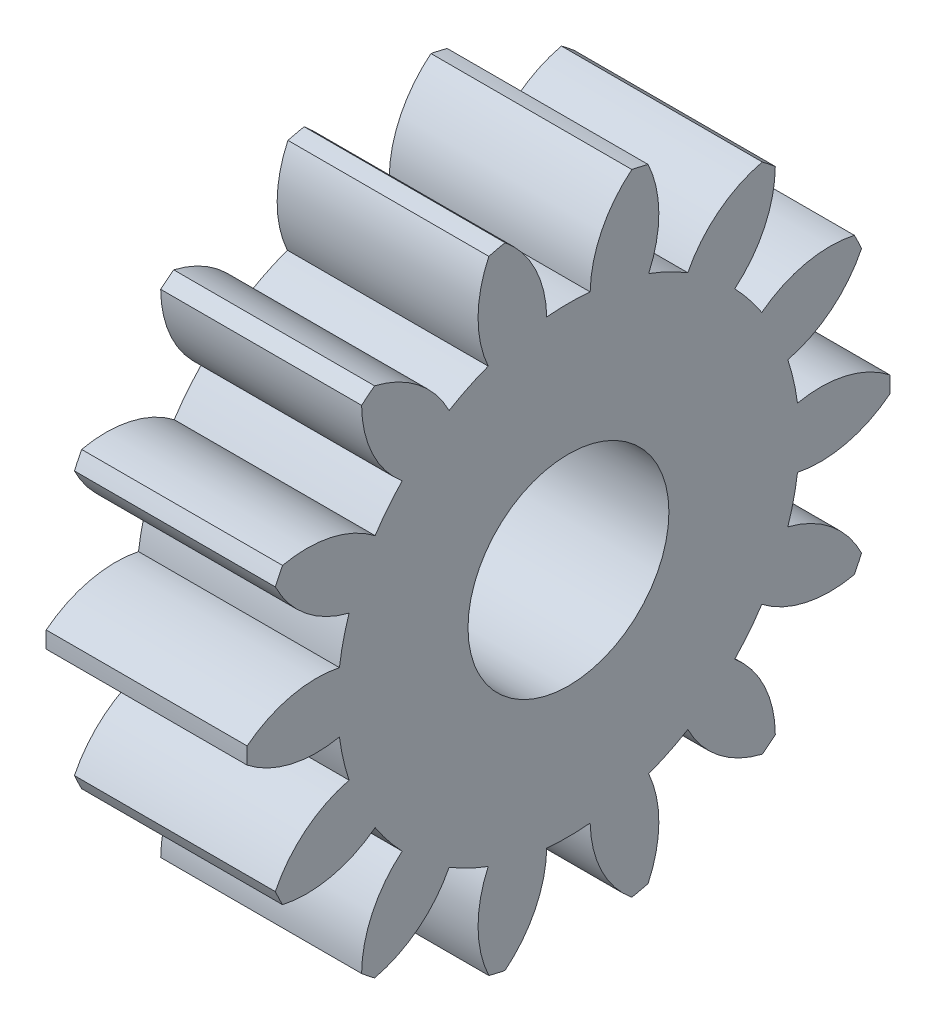
SolidWorks part; units mm, degrees
ref_plane "Plane1" through (0, 0, 0) normal (0, 0, 1) x (1, 0, 0)
ref_plane "Plane2" through (0, 0, 0) normal (0, 1, 0) x (1, 0, 0)
ref_plane "Plane3" through (0, 0, 0) normal (1, 0, 0) x (0, 0, -1)
sketch "HoldingSke" plane through (0, 0, 0) normal (0, 1, 0) x (1, 0, 0)
  line L0 (0, 0) -> (0.9703, -0.2419)
  line L1 (-15, 0) -> (100, 0) construction
  line L2 (0, 0) -> (-2.1039, 2.3779)
  line L3 (0, 0) -> (-11.863, 4.5341)
  line L4 (0, 0) -> (8.3795, 2.0892)
  line L5 (0, 0) -> (-46.8476, -17.4728)
  line L6 (0, 0) -> (-4.1448, -2.7965)
  line L7 (-2.1039, 2.3779) -> (8.6586, 51.2059)
  line L8 (-76.2, 54.61) -> (-75.3, 54.61)
  line L9 (-71.009, 38.7566) -> (-53.1078, 45.2721)
  line L10 (-76.2, 71.12) -> (104.1128, 71.12)
  line L11 (0, 0) -> (-5, 0)
  line L12 (-76.2, 101.6) -> (-76.162, 101.6)
  line L13 (24.9733, 27.94) -> (52.9518, 28.4284)
  line L14 (24.9733, 27.94) -> (24.9743, 27.94)
  line L15 (24.9733, 27.94) -> (100.4006, 29.5858)
  line L16 (-63.627, -1) -> (-12.827, -1)
  circle A0 centre (0, 0) radius 2.5
  circle A1 centre (0, 0) radius 5.749
  circle A2 centre (0, 0) radius 37.5
  circle A3 centre (0, 0) radius 2.5
  dimension "MHD" = 11.498
  dimension "Hub_dia" = 75
  dimension "Bore" = 5
  dimension "MBD" = 5
  dimension "Num_teeth" = 14
  dimension "Pitch" = 1
  dimension "Overall_len" = 50
  dimension "Show_teeth" = 14
  dimension "Thickness" = 5
  dimension "OAL" = 50.0001
  dimension "T_dim" = 0.9
  dimension "Ap" = 20
  dimension "H" = 19.05
  dimension "Pitch_radius" = 180.3128
  dimension "Width" = 5
  dimension "Backlash" = 0.038
  dimension "Addendum_fac" = 1
  dimension "Dedendum_fac" = 1.25
  dimension "Clearance_fac" = 0.25
  dimension "Dedendum_add" = 0.001
  dimension "Module" = 1
sketch "BasProSke" plane through (0, 0, 0) normal (0, 1, 0) x (1, 0, 0)
  line L0 (-10, 0) -> (60, 0) construction
  line L1 (0, 0) -> (0, 8)
  line L2 (0, 0) -> (5, 0)
  line L3 (5, 0) -> (5, 8)
  line L4 (5, 8) -> (0, 8)
  dimension "Thickness" = 5
  dimension "Diameter" = 16
revolve "Base-Revolve" add sketch "BasProSke" angle 360 about L0
sketch "TooCutSke" plane through (0, 0, 0) normal (1, 0, 0) x (0, 0, -1)
  line L1 (0, 0) -> (0, 107) construction
  line L2 (0, 0) -> (-0.8502, 6.9482) construction
  line L3 (0, 0) -> (-3.0989, 13.5772) construction
  line L4 (-0.8502, 6.9482) -> (-1.5494, 6.7886) construction
  arc A0 (0.5404, 5.7235) -> (-0.5404, 5.7235) centre (0, 0) ccw
  arc A1 (1.6036, 7.8636) -> (-1.6036, 7.8636) centre (0, 0) ccw
  circle A2 centre (0, 0) radius 7 construction
  circle A3 centre (0, 0) radius 6.5778 construction
  arc A4 (-0.5404, 5.7235) -> (-1.6036, 7.8636) centre (-3.3398, 5.6669) ccw
  arc A5 (1.6036, 7.8636) -> (0.5404, 5.7235) centre (3.3398, 5.6669) ccw
  dimension "Root_dia" = 11.498
  dimension "Overcut_dia" = 16.0508
  dimension "Pitch_dia" = 14
  dimension "Base_dia" = 13.1557
  dimension "Flank_rad" = 2.8
  dimension "Half_ang" = 12.857
  dimension "Half_CT" = 0.7173
extrude "ToothCut" cut sketch "TooCutSke" along normal through all
fillet "Breaks" [suppressed] radius 0.02
fillet "RootFillets" [suppressed] radius 0.251
pattern_circular "TeethCuts" count 14 every 25.714 about axis through (-10, 0, 0) along (1, 0, 0) of "ToothCut", "RootFillets", "Breaks"
sketch "HubNeaOneSke" plane through (0, 0, 0) normal (-1, 0, 0) x (0, 0, 1)
  circle A0 centre (0, 0) radius 5.749
  dimension "Diameter" = 11.498
extrude "HubNearOne" [suppressed] add sketch "HubNeaOneSke" along normal blind 45.0001
sketch "HubNeaBotSke" plane through (0, 0, 0) normal (-1, 0, 0) x (0, 0, 1)
  circle A0 centre (0, 0) radius 5.749
  dimension "Diameter" = 11.498
extrude "HubNearBoth" [suppressed] add sketch "HubNeaBotSke" along normal blind 22.5
ref_plane "FarPln" through (5, 0, 0) normal (1, 0, 0) x (0, 0, -1)
sketch "HubFarSke" plane through (5, 0, 0) normal (1, 0, 0) x (0, 0, -1)
  circle A0 centre (0, 0) radius 5.749
  dimension "Diameter" = 11.498
extrude "HubFar" [suppressed] add sketch "HubFarSke" along normal blind 22.5
sketch "BorSke" plane through (0, 0, 0) normal (1, 0, 0) x (0, 0, -1)
  circle A0 centre (0, 0) radius 2.5
  dimension "Diameter" = 5
extrude "Bore" cut sketch "BorSke" along normal mid plane 100.0001
sketch "KeySke" plane through (0, 0, 0) normal (1, 0, 0) x (0, 0, -1)
  line L0 (-1, 0) -> (-1, 3.4)
  line L1 (-1, 3.4) -> (1, 3.4)
  line L2 (1, 3.4) -> (1, 0)
  line L3 (0, 0) -> (0, 34) construction
  line L4 (-1, 0) -> (1, 0)
  dimension "Offset" = 3.4
  dimension "Width" = 2
extrude "Keyway" [suppressed] cut sketch "KeySke" along normal mid plane 100.0001
pattern_circular "Keyway2" [suppressed] count 2 every 90 about axis through (-10, 0, 0) along (1, 0, 0)
equation "' \"Module@HoldingSke\" = 6.35"
equation "' \"Num_teeth@HoldingSke\" = 12"
equation "' \"Ap@HoldingSke\" =  20"
equation "' \"Ap@HoldingSke\" = 20"
equation "' \"Width@HoldingSke\" = 0.5 * 25.4"
equation "' \"Hub_dia@HoldingSke\"= 1 * 25.4"
equation "' \"Hub_dia@HoldingSke\" = 1 * 25.4"
equation "' \"Overall_len@HoldingSke\" = 1.0 * 25.4"
equation "' \"Bore@HoldingSke\" = 0.75 * 25.4"
equation "' \"T_dim@HoldingSke\" = 0.1 * 25.4"
equation "' \"Width@KeySke\" = 0.25 * 25.4"
equation "' \"Show_teeth@HoldingSke\" = 13"
equation "' \"Backlash@HoldingSke\" = 0.009 * 25.4"
equation "' \"Addendum_fac@HoldingSke\" = 1.0"
equation "' \"Dedendum_fac@HoldingSke\" = 1.25"
equation "' \"Dedendum_add@HoldingSke\" = 0.00005 * 25.4"
equation "' \"Clearance_fac@HoldingSke\" = 0.25"
equation "\"Pitch@HoldingSke\" = 1 / \"Module@HoldingSke\""
equation "\"Overcut_dia@TooCutSke\" = (\"Num_teeth@HoldingSke\" + 2 * \"Addendum_fac@HoldingSke\") / \"Pitch@HoldingSke\" + 0.002 * 25.4"
equation "\"Pitch_dia@TooCutSke\" = \"Num_teeth@HoldingSke\" / \"Pitch@HoldingSke\""
equation "\"Base_dia@TooCutSke\" = \"Num_teeth@HoldingSke\" / \"Pitch@HoldingSke\" * cos((\"Ap@HoldingSke\"  * 3.14159265 / 180))"
equation "\"Root_dia@TooCutSke\" = (\"Num_teeth@HoldingSke\" + 2) / \"Pitch@HoldingSke\" - 2 * (\"Addendum_fac@HoldingSke\" + \"Dedendum_fac@HoldingSke\") / \"Pitch@HoldingSke\" - \"Dedendum_add@HoldingSke\" * 2"
equation "\"Half_ang@TooCutSke\" = 180 / \"Num_teeth@HoldingSke\""
equation "\"Half_CT@TooCutSke\" = \"Num_teeth@HoldingSke\" / \"Pitch@HoldingSke\" * sin((3.14159265 / 2 / \"Num_teeth@HoldingSke\")) / 2 - 7 * \"Backlash@HoldingSke\" / 4"
equation "\"Flank_rad@TooCutSke\" = \"Num_teeth@HoldingSke\" / \"Pitch@HoldingSke\" / 5"
equation "\"Radius@RootFillets\" = \"Clearance_fac@HoldingSke\" / \"Pitch@HoldingSke\" + \"Dedendum_add@HoldingSke\""
equation "\"Break_rad@Breaks\" = 0.02 / \"Pitch@HoldingSke\""
equation "\"Thickness@HoldingSke\" = \"Width@HoldingSke\""
equation "\"OAL@HoldingSke\" = \"Thickness@HoldingSke\""
equation "\"MHD@HoldingSke\" = (\"Num_teeth@HoldingSke\" + 2) / \"Pitch@HoldingSke\" - 2 * (\"Addendum_fac@HoldingSke\" + \"Dedendum_fac@HoldingSke\")  / \"Pitch@HoldingSke\" - \"Dedendum_add@HoldingSke\" * 2"
equation "\"MBD@HoldingSke\" = (\"Num_teeth@HoldingSke\" + 2) / \"Pitch@HoldingSke\" - 2 * (\"Addendum_fac@HoldingSke\" + \"Dedendum_fac@HoldingSke\")  / \"Pitch@HoldingSke\" - \"Dedendum_add@HoldingSke\" * 2 - 0.002 * 25.4"
equation "\"MHD@HoldingSke\" = ((sgn( \"MHD@HoldingSke\" - \"Hub_dia@HoldingSke\" )-1)*( \"MHD@HoldingSke\" - \"Hub_dia@HoldingSke\" ))/-2+ \"Hub_dia@HoldingSke\""
equation "\"MBD@HoldingSke\" = ((sgn( \"MBD@HoldingSke\" - \"Bore@HoldingSke\" )-1)*( \"MBD@HoldingSke\" - \"Bore@HoldingSke\" ))/-2+ \"Bore@HoldingSke\""
equation "\"OAL@HoldingSke\" = ((sgn( \"OAL@HoldingSke\" - \"Overall_len@HoldingSke\" )+1)*( \"OAL@HoldingSke\" - \"Overall_len@HoldingSke\" ))/2 + \"Overall_len@HoldingSke\" + 0.000002 * 25.4"
equation "\"Num_teeth@TeethCuts\" = int( \"Show_teeth@HoldingSke\" ) + 1"
equation "\"Num_teeth@TeethCuts\" = ((sgn( \"Num_teeth@TeethCuts\" - \"Num_teeth@HoldingSke\" )-1)*( \"Num_teeth@TeethCuts\" - \"Num_teeth@HoldingSke\" ))/-2+ \"Num_teeth@HoldingSke\""
equation "\"Num_teeth@TeethCuts\" = ((sgn( \"Num_teeth@TeethCuts\" - 2.0)+1)*( \"Num_teeth@TeethCuts\" - 2.0))/2 +2.0"
equation "\"Angle@TeethCuts\" = 360.0 / \"Num_teeth@HoldingSke\""
equation "\"Diameter@BasProSke\" = (\"Num_teeth@HoldingSke\" + 2 * \"Addendum_fac@HoldingSke\") / \"Pitch@HoldingSke\""
equation "\"Thickness@BasProSke\"  = \"Thickness@HoldingSke\""
equation "' \"Fillet_rad@BasProSke\" =  \"Thickness@HoldingSke\" * 0.05"
equation "' \"Fillet_rad@BasProSke\" = \"Thickness@HoldingSke\" * 0.05"
equation "\"MHD@HoldingSke\" = ((sgn( \"MHD@HoldingSke\" - \"Root_dia@TooCutSke\" )-1)*( \"MHD@HoldingSke\" - \"Root_dia@TooCutSke\" ))/-2+ \"Root_dia@TooCutSke\""
equation "\"Diameter@HubNeaOneSke\" = \"MHD@HoldingSke\""
equation "\"Length@HubNearOne\" = \"OAL@HoldingSke\" - \"Thickness@BasProSke\""
equation "\"Diameter@HubNeaBotSke\" = \"MHD@HoldingSke\""
equation "\"Length@HubNearBoth\" = ( \"OAL@HoldingSke\" - \"Thickness@BasProSke\" ) / 2.0"
equation "\"Thickness@FarPln\" = \"Thickness@BasProSke\""
equation "\"Diameter@HubFarSke\" = \"MHD@HoldingSke\""
equation "\"Length@HubFar\" = ( \"OAL@HoldingSke\" - \"Thickness@BasProSke\" ) / 2.0"
equation "\"Diameter@BorSke\" = \"MBD@HoldingSke\""
equation "\"D1@Bore\" = \"OAL@HoldingSke\" * 2.0"
equation "\"D1@Keyway\" = \"OAL@HoldingSke\" * 2.0"
equation "\"Offset@KeySke\" = \"T_dim@HoldingSke\" + \"MBD@HoldingSke\" / 2.0"
